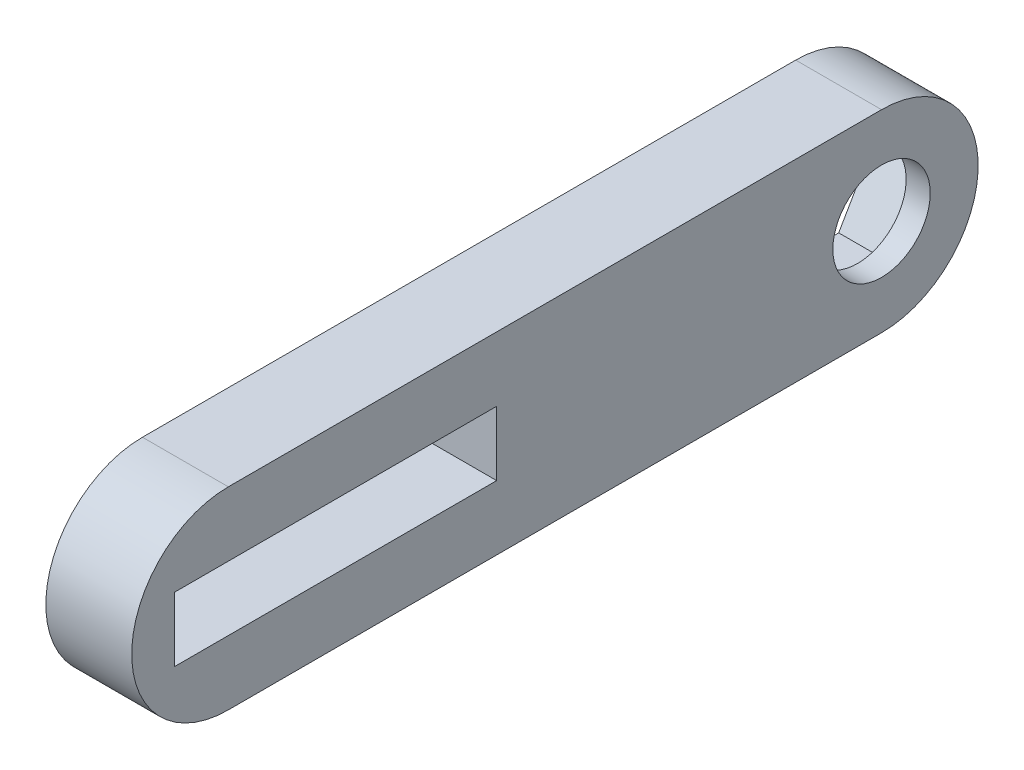
SolidWorks part; units mm, degrees
ref_plane "Front Plane" through (0, 0, 0) normal (0, 0, 1) x (1, 0, 0)
ref_plane "Top Plane" through (0, 0, 0) normal (0, 1, 0) x (1, 0, 0)
ref_plane "Right Plane" through (0, 0, 0) normal (1, 0, 0) x (0, 0, -1)
sketch "Sketch1" plane through (0, 0, 0) normal (1, 0, 0) x (0, 0, -1)
  line L0 (-12.0755, 0) -> (12.0755, 0) construction
  line L1 (-12.0755, 3.5719) -> (12.0755, 3.5719)
  line L2 (-12.0755, -3.5719) -> (12.0755, -3.5719)
  arc A0 (-12.0755, 3.5719) -> (-12.0755, -3.5719) centre (-12.0755, 0) ccw
  arc A1 (12.0755, -3.5719) -> (12.0755, 3.5719) centre (12.0755, 0) ccw
  point P2 (0, 0)
  dimension "D2" = 31.2947
  dimension "D1" = 7.1438
extrude "Boss-Extrude1" add sketch "Sketch1" along normal blind 3.175
sketch "Sketch2" plane through (0, 0, 0) normal (-1, 0, 0) x (0, 0, 1)
  point P0 (-12.0755, 0)
hole_wizard "M3 Clearance Hole1" positions "Sketch3" profile "Sketch5" hole size "M3" standard "ANSI Metric"
sketch "Sketch3" plane through (0, 0, 0) normal (-1, 0, 0) x (0, 0, 1)
  point P0 (-12.0755, 0)
sketch "Sketch5" plane through (0, 0, -12.0755) normal (0, 1, 0) x (0, 0, 1)
  line L0 (0, 0) -> (0, 8.7015)
  line L1 (0, 8.7015) -> (1.8, 7.62)
  line L2 (1.8, 7.62) -> (1.8, 0)
  line L5 (1.8, 0) -> (0, 0)
  line L10 (0, 8.7015) -> (-1.8, 7.62) construction
  line L11 (0, -6.35) -> (0, 107.95) construction
  dimension "Hole Dia." = 3.6
  dimension "Hole Depth" = 7.62
  dimension "Drill Angle" = 118
sketch "Sketch6" plane through (3.175, 0, 0) normal (1, 0, 0) x (0, 0, -1)
  point P0 (-12.0755, 0)
hole_wizard "CSK for M3 Flat Head Machine Screw2" positions "Sketch7" profile "Sketch8" countersink size "M3" standard "ANSI Metric"
sketch "Sketch7" plane through (3.175, 0, 0) normal (1, 0, 0) x (0, 0, -1)
  point P0 (-12.3031, 0)
sketch "Sketch8" plane through (3.175, 0, 12.3031) normal (0, 1, 0) x (0, 0, -1)
  line L0 (0, 0) -> (0, 8.6415)
  line L1 (0, 8.6415) -> (1.7, 7.62)
  line L2 (1.7, 7.62) -> (1.7, 1.45)
  line L3 (1.7, 1.45) -> (3.15, 0)
  line L5 (3.15, 0) -> (0, 0)
  line L6 (-1.7, 1.45) -> (-3.15, 0) construction
  line L10 (0, 8.6415) -> (-1.7, 7.62) construction
  line L11 (0, -6.35) -> (0, 107.95) construction
  dimension "Hole Dia." = 3.4
  dimension "Hole Depth" = 7.62
  dimension "Near C'Sink Dia." = 6.3
  dimension "Near C'Sink Angle" = 90
  dimension "Drill Angle" = 118
sketch "Sketch9" plane through (0, 0, 0) normal (-1, 0, 0) x (0, 0, 1)
  line L0 (15.6474, 0) -> (0, 0) construction
  line L2 (2.1536, -1.1906) -> (14.0599, -1.1906)
  line L3 (2.1536, -1.1906) -> (2.1536, 1.1906)
  line L4 (2.1536, 1.1906) -> (14.0599, 1.1906)
  line L5 (14.0599, -1.1906) -> (14.0599, 1.1906)
  line L6 (8.1067, 1.1906) -> (8.1067, -1.1906) construction
  line L7 (2.1536, 0) -> (14.0599, 0) construction
  arc A0 (12.0755, -3.5719) -> (12.0755, 3.5719) centre (12.0755, 0) ccw construction
  point P6 (8.1067, 0)
  dimension "D1" = 1.5875
  dimension "D2" = 2.3813
  dimension "D3" = 11.9062
extrude "Cut-Extrude1" cut sketch "Sketch9" against normal through all
sketch "Sketch10" plane through (0, 0, 0) normal (-1, 0, 0) x (0, 0, 1)
  line L1 (-10.4844, -2.7559) -> (-8.8932, 0)
  line L2 (-8.8932, 0) -> (-10.4844, 2.7559)
  line L3 (-10.4844, 2.7559) -> (-13.6666, 2.7559)
  line L4 (-13.6666, 2.7559) -> (-15.2577, 0)
  line L5 (-15.2577, 0) -> (-13.6666, -2.7559)
  line L6 (-13.6666, -2.7559) -> (-10.4844, -2.7559)
  circle A0 centre (-12.0755, 0) radius 2.7559 construction
  dimension "D1" = 5.5118
extrude "Cut-Extrude2" cut sketch "Sketch10" against normal blind 2.286
